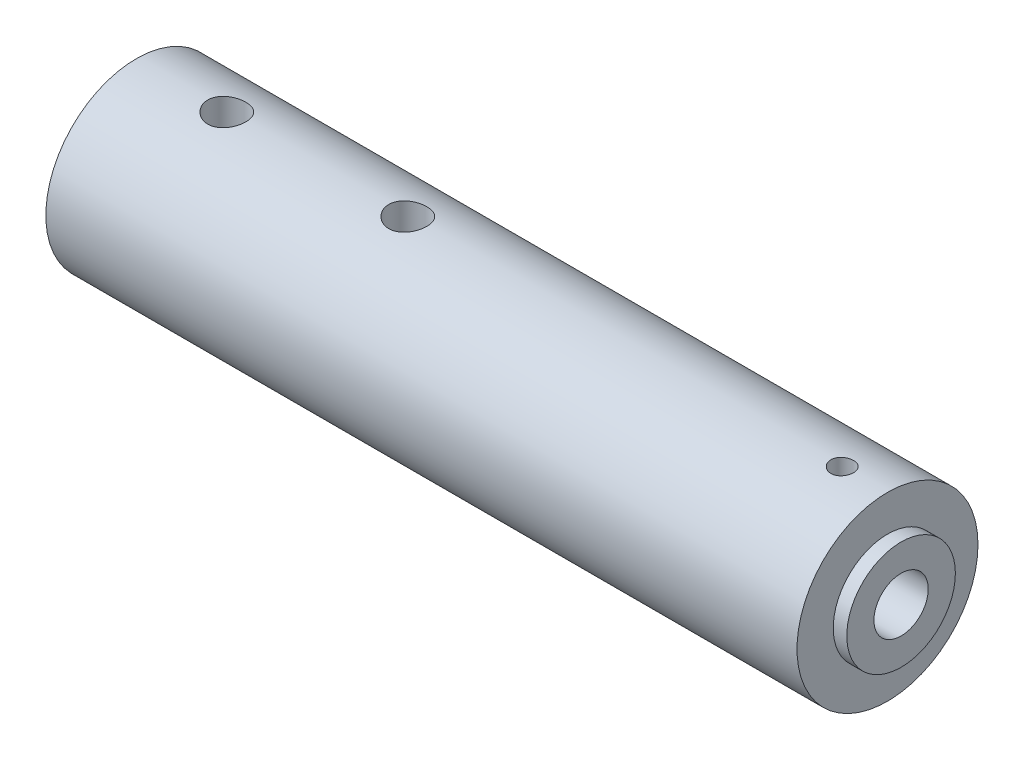
SolidWorks part; units mm, degrees
ref_plane "Plan de face" through (0, 0, 0) normal (0, 0, 1) x (1, 0, 0)
ref_plane "Plan de dessus" through (0, 0, 0) normal (0, 1, 0) x (1, 0, 0)
ref_plane "Plan de droite" through (0, 0, 0) normal (1, 0, 0) x (0, 0, -1)
sketch "Esquisse1" plane through (0, 0, 0) normal (1, 0, 0) x (0, 0, -1)
  circle A0 centre (0, 0) radius 10
  dimension "D1" = 20
extrude "Boss.-Extru.1" add sketch "Esquisse1" along normal blind 83
sketch "Esquisse2" plane through (83, 0, 0) normal (1, 0, 0) x (0, 0, -1)
  circle A0 centre (0, 0) radius 6
  dimension "D1" = 12
extrude "Boss.-Extru.2" add sketch "Esquisse2" along normal blind 1.5
sketch "Esquisse5" plane through (84.5, 0, 0) normal (1, 0, 0) x (0, 0, -1)
  circle A0 centre (0, 0) radius 3
  dimension "D1" = 6
extrude "Enlèv. mat.-Extru.2" cut sketch "Esquisse5" against normal blind 25
hole_wizard "Trou taraudé M31" positions "Esquisse8" profile "Esquisse9" tap size "M3" standard "ISO"
sketch "Esquisse8" plane through (0, 0, 0) normal (0, 1, 0) x (1, 0, 0)
  line L0 (83, -10) -> (83, 10) construction
  point P0 (78, 0)
  dimension "D1" = 5
sketch "Esquisse9" plane through (78, 0, 0) normal (1, 0, 0) x (0, 0, -1)
  line L0 (0, 0) -> (0, 10)
  line L1 (0, 10) -> (1.25, 10)
  line L2 (1.25, 10) -> (1.25, 0)
  line L5 (1.25, 0) -> (0, 0)
  line L11 (0, -6.35) -> (0, 107.95) construction
  dimension "Diamètre principal du filetage" = 2.5
  dimension "Profondeur du trou pour taraudage jusqu'au prochain" = 10
hole_wizard "Trou taraudé M53" positions "Esquisse17" profile "Esquisse18" tap size "M5" standard "ISO"
sketch "Esquisse17" plane through (0, 0, 0) normal (0, 1, 0) x (1, 0, 0)
  point P0 (10, 0)
  point P2 (30, 0)
  dimension "D1" = 10
  dimension "D2" = 30
sketch "Esquisse18" plane through (10, 0, 0) normal (1, 0, 0) x (0, 0, -1)
  line L0 (0, 0) -> (0, 10)
  line L1 (0, 10) -> (2.1, 10)
  line L2 (2.1, 10) -> (2.1, 0)
  line L5 (2.1, 0) -> (0, 0)
  line L11 (0, -6.35) -> (0, 107.95) construction
  dimension "Diamètre principal du filetage" = 4.2
  dimension "Profondeur du trou pour taraudage jusqu'au prochain" = 10
sketch "Esquisse19" plane through (0, 0, 0) normal (0, 1, 0) x (1, 0, 0)
  circle A0 centre (10, 0) radius 2.5
  circle A1 centre (30, 0) radius 2.5
  dimension "D1" = 5
  dimension "D2" = 5
  dimension "D3" = 10
  dimension "D4" = 30
extrude "Enlèv. mat.-Extru.3" cut sketch "Esquisse19" against normal through all
